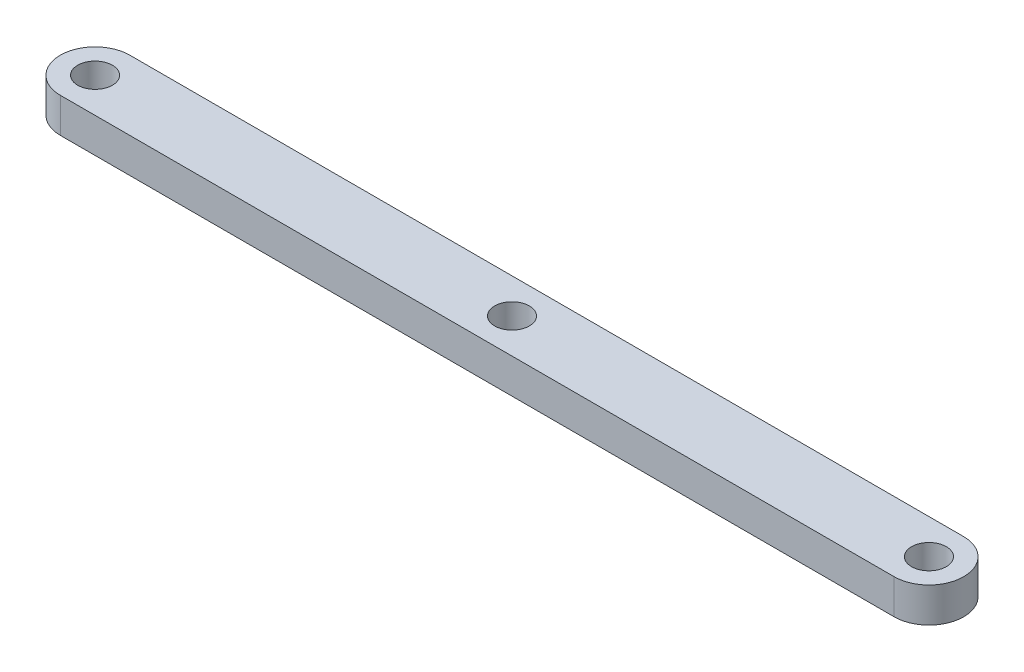
SolidWorks part; units mm, degrees
ref_plane "Front Plane" through (0, 0, 0) normal (0, 0, 1) x (1, 0, 0)
ref_plane "Top Plane" through (0, 0, 0) normal (0, 1, 0) x (1, 0, 0)
ref_plane "Right Plane" through (0, 0, 0) normal (1, 0, 0) x (0, 0, -1)
sketch "Sketch1" plane through (0, 0, 0) normal (0, 1, 0) x (1, 0, 0)
  line L0 (0, 0) -> (-152.4, 0) construction
  line L1 (0, -6.35) -> (-152.4, -6.35)
  line L2 (0, 6.35) -> (-152.4, 6.35)
  arc A0 (0, -6.35) -> (0, 6.35) centre (0, 0) ccw
  arc A1 (-152.4, 6.35) -> (-152.4, -6.35) centre (-152.4, 0) ccw
  point P3 (-76.2, 0)
  dimension "D1" = 6.35
  dimension "D2" = 152.4
extrude "Boss-Extrude1" add sketch "Sketch1" along normal blind 6.35
sketch "Sketch2" plane through (0, 6.35, 0) normal (0, 1, 0) x (1, 0, 0)
  line L0 (-152.4, 0) -> (0, 0) construction
  circle A0 centre (-152.4, 0) radius 3.175
  arc A1 (-152.4, 6.35) -> (-152.4, -6.35) centre (-152.4, 0) ccw construction
  circle A2 centre (0, 0) radius 3.175
  circle A3 centre (-76.2, 0) radius 3.175
  point P10 (-76.2, 0)
  dimension "D1" = 6.35
extrude "Cut-Extrude1" cut sketch "Sketch2" against normal through all
